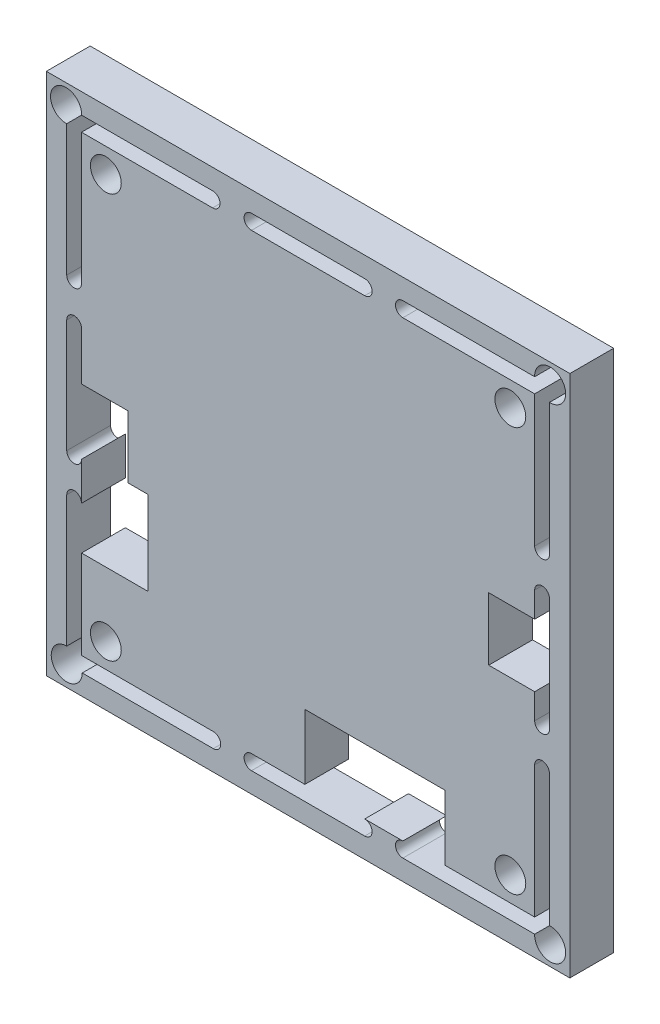
SolidWorks part; units mm, degrees
ref_plane "Front Plane" through (0, 0, 0) normal (0, 0, 1) x (1, 0, 0)
ref_plane "Top Plane" through (0, 0, 0) normal (0, 1, 0) x (1, 0, 0)
ref_plane "Right Plane" through (0, 0, 0) normal (1, 0, 0) x (0, 0, -1)
sketch "Sketch1" plane through (0, 0, 0) normal (0, 0, 1) x (1, 0, 0)
  line L1 (0, 37.9349) -> (37.9349, 37.9349)
  line L2 (0, 37.9349) -> (0, 0)
  line L3 (0, 0) -> (37.9349, 0)
  line L4 (37.9349, 37.9349) -> (37.9349, 0)
  dimension "D1" = 37.9349
extrude "Boss-Extrude1" add sketch "Sketch1" along normal blind 3.175
sketch "Sketch9" plane through (0, 0, 3.175) normal (0, 0, 1) x (1, 0, 0)
  line L0 (33.6232, 33.6232) -> (35.9219, 33.6232) construction
  line L1 (0, 0) -> (37.9349, 0) construction
  line L2 (2.5493, 18.9674) -> (1.4766, 18.9675) construction
  line L3 (33.6232, 35.922) -> (33.6232, 33.6232) construction
  line L4 (0, 37.9349) -> (0, 0) construction
  line L5 (35.3856, 12.1002) -> (36.4583, 12.1002) construction
  line L6 (4.3117, 35.9219) -> (4.3117, 33.6232) construction
  line L7 (2.013, 33.6232) -> (4.3117, 33.6232) construction
  line L8 (4.3117, 2.013) -> (4.3117, 4.3117) construction
  line L9 (2.0129, 4.3117) -> (4.3117, 4.3117) construction
  line L10 (35.9219, 4.3117) -> (33.6232, 4.3117) construction
  line L11 (33.6232, 2.013) -> (33.6232, 4.3117) construction
  line L12 (35.3856, 12.1002) -> (35.3856, 2.5493)
  line L13 (35.3856, 2.5493) -> (25.8347, 2.5493)
  line L14 (35.3856, 1.4766) -> (25.8347, 1.4766)
  line L15 (35.3856, 36.4583) -> (25.8347, 36.4583)
  line L16 (37.9349, 37.9349) -> (0, 37.9349) construction
  line L17 (12.0489, 36.4583) -> (2.5493, 36.4583)
  line L18 (12.0489, 36.4583) -> (12.0489, 35.3856) construction
  line L19 (12.0489, 35.3856) -> (2.5493, 35.3856)
  line L20 (35.922, 35.9219) -> (2.0129, 35.9219) construction
  line L21 (23.0695, 36.4583) -> (14.8653, 36.4583)
  line L22 (35.922, 35.9219) -> (35.922, 2.013) construction
  line L23 (35.922, 2.013) -> (2.013, 2.013) construction
  line L24 (2.0129, 35.9219) -> (2.013, 2.013) construction
  line L25 (18.9674, 37.9349) -> (18.9674, 0) construction
  line L26 (23.0695, 36.4583) -> (23.0695, 35.3856) construction
  line L27 (23.0695, 35.3856) -> (14.8653, 35.3856)
  line L28 (0, 0) -> (37.9349, 0) construction
  line L29 (25.8347, 2.5493) -> (25.8347, 1.4766) construction
  line L30 (14.8653, 36.4583) -> (14.8653, 35.3856) construction
  line L31 (35.3856, 2.5493) -> (36.4583, 2.5493) construction
  line L32 (35.922, 18.9674) -> (2.013, 18.9674) construction
  line L33 (2.5493, 36.4583) -> (2.5493, 35.3856) construction
  line L34 (2.5493, 35.3856) -> (1.4766, 35.3856) construction
  line L35 (2.5493, 12.1002) -> (1.4766, 12.1002) construction
  line L36 (36.4583, 12.1002) -> (36.4583, 2.5493)
  line L37 (35.3856, 35.3856) -> (25.8347, 35.3856)
  line L38 (2.5493, 35.3856) -> (2.5493, 25.886)
  line L39 (12.1002, 2.5493) -> (12.1002, 1.4766) construction
  line L42 (25.8347, 36.4583) -> (25.8347, 35.3856) construction
  line L43 (35.3856, 35.3856) -> (36.4583, 35.3856) construction
  line L44 (35.3856, 35.3856) -> (35.3856, 25.8347)
  line L45 (35.3856, 25.8347) -> (36.4583, 25.8347) construction
  line L46 (36.4583, 35.3856) -> (36.4583, 25.8347)
  line L47 (2.5493, 25.886) -> (1.4766, 25.886) construction
  line L48 (1.4766, 35.3856) -> (1.4766, 25.886)
  line L49 (2.5493, 23.0696) -> (1.4766, 23.0696) construction
  line L50 (2.5493, 23.0696) -> (2.5493, 14.8654)
  line L51 (2.5493, 14.8654) -> (1.4766, 14.8654) construction
  line L52 (1.4766, 23.0696) -> (1.4766, 14.8654)
  line L53 (36.4583, 18.9675) -> (35.3856, 18.9675) construction
  line L54 (36.4583, 23.0695) -> (35.3856, 23.0695) construction
  line L55 (36.4583, 23.0695) -> (36.4583, 14.8654)
  line L56 (36.4583, 14.8654) -> (35.3856, 14.8654) construction
  line L57 (35.3856, 23.0695) -> (35.3856, 14.8654)
  line L58 (18.9674, 36.4583) -> (18.9674, 35.3856) construction
  line L59 (18.9674, 2.5493) -> (18.9674, 1.4766) construction
  line L60 (23.0695, 2.5493) -> (14.8653, 2.5493)
  line L61 (23.0695, 2.5493) -> (23.0695, 1.4766) construction
  line L62 (23.0695, 1.4766) -> (14.8653, 1.4766)
  line L63 (14.8653, 2.5493) -> (14.8653, 1.4766) construction
  line L68 (2.5493, 12.1002) -> (2.5493, 2.5493)
  line L69 (1.4766, 12.1002) -> (1.4766, 2.6006)
  line L70 (2.5493, 2.5493) -> (12.1002, 2.5493)
  line L71 (2.6006, 1.4766) -> (12.1002, 1.4766)
  line L75 (12.1002, 2.013) -> (12.6365, 2.013) construction
  line L76 (2.013, 2.013) -> (2.013, 0) construction
  line L77 (0, 2.0129) -> (2.013, 2.013) construction
  circle A0 centre (33.6232, 33.6232) radius 1.1176
  circle A1 centre (4.3117, 33.6232) radius 1.1176
  circle A2 centre (4.3117, 4.3117) radius 1.1176
  circle A3 centre (33.6232, 4.3117) radius 1.1176
  arc A4 (25.8347, 1.4766) -> (25.8347, 2.5493) centre (25.8347, 2.013) cw
  arc A5 (36.4583, 2.5493) -> (35.3856, 1.4766) centre (36.5084, 1.4265) cw
  arc A6 (14.8653, 36.4583) -> (14.8653, 35.3856) centre (14.8653, 35.9219) ccw
  arc A7 (23.0695, 36.4583) -> (23.0695, 35.3856) centre (23.0695, 35.9219) cw
  arc A8 (1.4766, 2.6006) -> (2.6006, 1.4766) centre (1.4766, 1.4766) ccw
  arc A9 (36.4583, 12.1002) -> (35.3856, 12.1002) centre (35.9219, 12.1002) ccw
  arc A10 (12.0489, 35.3856) -> (12.0489, 36.4583) centre (12.0489, 35.9219) ccw
  arc A11 (1.4766, 35.3856) -> (2.5493, 36.4583) centre (1.4265, 36.5084) cw
  arc A12 (36.4583, 25.8347) -> (35.3856, 25.8347) centre (35.922, 25.8347) cw
  arc A13 (25.8347, 35.3856) -> (25.8347, 36.4583) centre (25.8347, 35.9219) cw
  arc A14 (36.4583, 35.3856) -> (35.3856, 36.4583) centre (36.5084, 36.5084) ccw
  arc A15 (2.5493, 25.886) -> (1.4766, 25.886) centre (2.013, 25.886) cw
  arc A16 (2.5493, 23.0696) -> (1.4766, 23.0696) centre (2.0129, 23.0695) ccw
  arc A17 (1.4766, 14.8654) -> (2.5493, 14.8654) centre (2.0129, 14.8654) ccw
  arc A18 (1.4766, 12.1002) -> (2.5493, 12.1002) centre (2.0129, 12.1002) cw
  arc A19 (12.1002, 2.5493) -> (12.1002, 1.4766) centre (12.1002, 2.013) cw
  arc A20 (36.4583, 23.0695) -> (35.3856, 23.0695) centre (35.922, 23.0695) ccw
  arc A21 (36.4583, 14.8654) -> (35.3856, 14.8654) centre (35.922, 14.8653) cw
  arc A22 (14.8653, 2.5493) -> (14.8653, 1.4766) centre (14.8654, 2.0129) ccw
  arc A23 (23.0695, 1.4766) -> (23.0695, 2.5493) centre (23.0695, 2.0129) ccw
  point P47 (18.9674, 18.9674)
  point P66 (2.0129, 18.9674)
  point P89 (35.922, 18.9674)
  dimension "D1" = 9.4996
  dimension "D3" = 2.013
  dimension "D4" = 2.2352
  dimension "D6" = 8.2042
  dimension "D5" = 1.1239
  dimension "D7" = 1.0727
  dimension "D2" = 2.2987
extrude "Cut-Extrude2" cut sketch "Sketch9" against normal up to surface (3.175 mm away) up to face at (18.9674, 18.9675, 0)
sketch "Sketch12" plane through (0, 0, 0) normal (0, 0, -1) x (-1, 0, 0)
  line L0 (-37.9349, 0) -> (-37.9349, 37.9349) construction
  line L1 (-35.3856, 21.2408) -> (-32.0582, 21.2408)
  line L2 (-35.3856, 21.2408) -> (-35.3856, 16.6942)
  line L3 (-35.3856, 16.6942) -> (-32.0582, 16.6942)
  line L4 (-32.0582, 21.2408) -> (-32.0582, 16.6942)
  line L5 (-37.9349, 37.9349) -> (0, 37.9349) construction
  line L6 (-35.3856, 14.8654) -> (-35.3856, 23.0695) construction
  point P10 (-35.3856, 18.9675)
  dimension "D1" = 3.3274
  dimension "D2" = 4.5466
sketch "Sketch13" plane through (0, 0, 0) normal (0, 0, -1) x (-1, 0, 0)
  line L1 (-28.8925, 7.261) -> (-18.7325, 7.261)
  line L2 (-28.8925, 7.261) -> (-28.8925, 2.5493)
  line L3 (-28.8925, 2.5493) -> (-18.7325, 2.5493)
  line L4 (-18.7325, 7.261) -> (-18.7325, 2.5493)
  line L5 (-37.9349, 0) -> (-37.9349, 37.9349) construction
  line L6 (0, 0) -> (-37.9349, 0) construction
  line L7 (-14.8653, 2.5493) -> (-23.0695, 2.5493) construction
  dimension "D1" = 10.16
  dimension "D2" = 4.7117
  dimension "D3" = 9.0424
sketch "Sketch14" plane through (0, 0, 0) normal (0, 0, -1) x (-1, 0, 0)
  line L0 (-37.9349, 0) -> (-37.9349, 37.9349) construction
  line L1 (-7.3499, 15.0622) -> (-2.5493, 15.0622)
  line L2 (-7.3499, 15.0622) -> (-7.3499, 8.9789)
  line L3 (-7.3499, 8.9789) -> (-2.5493, 8.9789)
  line L4 (-2.5493, 15.0622) -> (-2.5493, 8.9789)
  line L5 (-37.9349, 37.9349) -> (0, 37.9349) construction
  line L6 (-2.5493, 23.0696) -> (-2.5493, 14.8654) construction
  line L7 (0, 0) -> (-37.9349, 0) construction
  dimension "D1" = 8.9789
  dimension "D2" = 6.0833
  dimension "D3" = 4.8006
extrude "Cut-Extrude4" cut sketch "Sketch12" against normal up to surface (3.175 mm away) up to face at (18.9674, 2.0129, 3.175)
sketch "Sketch15" plane through (0, 0, 0) normal (0, 0, -1) x (-1, 0, 0)
  line L0 (-37.9349, 37.9349) -> (0, 37.9349) construction
  line L1 (-5.9021, 19.5834) -> (-2.5493, 19.5834)
  line L2 (-5.9021, 19.5834) -> (-5.9021, 15.0622)
  line L3 (-5.9021, 15.0622) -> (-2.5493, 15.0622)
  line L4 (-2.5493, 19.5834) -> (-2.5493, 15.0622)
  line L5 (0, 37.9349) -> (0, 0) construction
  line L6 (-2.5493, 12.1002) -> (-2.5493, 2.5493) construction
  line L8 (0, 0) -> (-37.9349, 0) construction
  dimension "D1" = 4.5212
  dimension "D2" = 3.3528
  dimension "D3" = 15.0622
extrude "Cut-Extrude3" cut sketch "Sketch15" against normal up to surface (3.175 mm away) up to face at (34.8219, 18.9674, 3.175)
extrude "Cut-Extrude5" cut sketch "Sketch13" against normal up to surface (3.175 mm away) up to face at (3.1193, 18.1451, 3.175)
extrude "Cut-Extrude6" cut sketch "Sketch14" against normal up to surface (3.175 mm away) up to face at (26.8472, 4.1086, 3.175)
